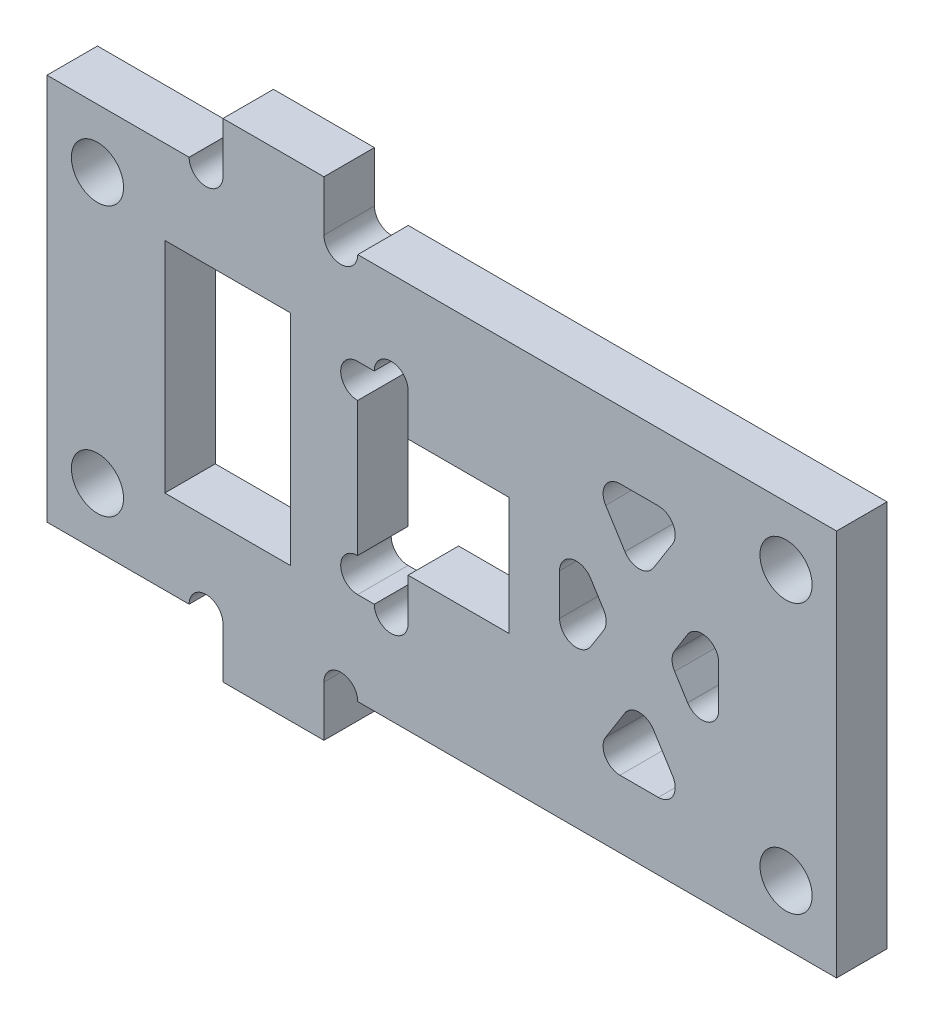
SolidWorks part; units mm, degrees
material "Thornel Mat VMA"
ref_plane "前视基准面" through (0, 0, 0) normal (0, 0, 1) x (1, 0, 0)
ref_plane "上视基准面" through (0, 0, 0) normal (0, 1, 0) x (1, 0, 0)
ref_plane "右视基准面" through (0, 0, 0) normal (1, 0, 0) x (0, 0, -1)
sketch "草图1" plane through (0, 0, 0) normal (0, 0, 1) x (1, 0, 0)
  line L0 (-13, 11.5) -> (-13, 14.5)
  line L1 (23.455, -11.5) -> (-7, -11.5)
  line L2 (23.455, -11.5) -> (23.455, 11.5)
  line L3 (23.455, 11.5) -> (-7, 11.5)
  line L4 (-23.455, -11.5) -> (-23.455, 11.5)
  line L5 (23.455, -11.5) -> (-23.455, 11.5) construction
  line L6 (23.455, 11.5) -> (-23.455, -11.5) construction
  line L7 (-20.455, 8) -> (-20.455, -8) construction
  line L8 (-20.455, 0) -> (0, 0) construction
  line L9 (0, 0) -> (0, 8.6559) construction
  line L10 (-2, -6) -> (-5, -6)
  line L11 (-2, -6) -> (-2, -3.5)
  line L12 (-2, 6) -> (-5, 6)
  line L13 (-5, -6) -> (-5, 6)
  line L14 (-2, -6) -> (-5, 6) construction
  line L15 (-2, 6) -> (-5, -6) construction
  line L16 (-13, 14.5) -> (-7, 14.5)
  line L17 (-7, 14.5) -> (-7, 11.5)
  line L18 (-13, 11.5) -> (-23.455, 11.5)
  line L19 (-7, -14.5) -> (-7, -11.5)
  line L20 (-13, -14.5) -> (-7, -14.5)
  line L21 (-13, -11.5) -> (-13, -14.5)
  line L22 (-13, -11.5) -> (-23.455, -11.5)
  line L23 (-2, -3.5) -> (4, -3.5)
  line L24 (4, -3.5) -> (4, 3.5)
  line L25 (4, 3.5) -> (-2, 3.5)
  line L26 (-2, 3.5) -> (-2, 6)
  line L27 (14.6819, -7.5) -> (11.7275, -2.813)
  line L28 (-9, 6.5) -> (-16.455, 6.5)
  line L29 (-9, 6.5) -> (-9, -6.5)
  line L30 (-9, -6.5) -> (-16.455, -6.5)
  line L31 (-16.455, 6.5) -> (-16.455, -6.5)
  line L32 (-9, 6.5) -> (-16.455, -6.5) construction
  line L33 (-9, -6.5) -> (-16.455, 6.5) construction
  line L34 (16.455, 7.5) -> (7, 7.5) construction
  line L35 (16.455, 7.5) -> (16.455, -7.5) construction
  line L36 (16.455, -7.5) -> (7, -7.5) construction
  line L37 (7, 7.5) -> (7, -7.5) construction
  line L38 (16.455, 7.5) -> (7, -7.5) construction
  line L39 (16.455, -7.5) -> (7, 7.5) construction
  line L40 (16.455, -4.687) -> (13.5006, 0)
  line L41 (7, -4.687) -> (9.9544, 0)
  line L42 (8.7731, -7.5) -> (11.7275, -2.813)
  line L43 (8.7731, -7.5) -> (14.6819, -7.5)
  line L44 (8.7731, 7.5) -> (14.6819, 7.5)
  line L45 (16.455, -4.687) -> (16.455, 4.687)
  line L46 (7, -4.687) -> (7, 4.687)
  line L47 (9.9544, 0) -> (7, 4.687)
  line L48 (13.5006, 0) -> (16.455, 4.687)
  line L49 (11.7275, 2.813) -> (8.7731, 7.5)
  line L50 (11.7275, 2.813) -> (14.6819, 7.5)
  circle A0 centre (-20.455, 8) radius 1.55
  circle A1 centre (-20.455, -8) radius 1.55
  circle A4 centre (20.455, -8) radius 1.55
  circle A5 centre (20.455, 8) radius 1.55
  circle A6 centre (-2, 4.995) radius 1.005 construction
  circle A7 centre (-5, 4.995) radius 1.005
  circle A8 centre (-5, -4.995) radius 1.005
  circle A9 centre (-2, -4.995) radius 1.005 construction
  circle A10 centre (-5.995, 11.5) radius 1.005
  circle A11 centre (-14.005, 11.5) radius 1.005
  circle A12 centre (-5.995, -11.5) radius 1.005
  circle A13 centre (-14.005, -11.5) radius 1.005
  circle A14 centre (-3.005, -6) radius 1.005
  circle A15 centre (-3.005, 6) radius 1.005
  point P0 (0, 0)
  point P7 (-3.5, 0)
  point P50 (-12.7275, 0)
  point P56 (11.7275, 0)
  dimension "D1" = 3.1
  dimension "D9" = 2.01
  dimension "D2" = 16
  dimension "D3" = 23
  dimension "D4" = 3
  dimension "D5" = 3
  dimension "D6" = 2
  dimension "D7" = 12
  dimension "D8" = 40.91
  dimension "D10" = 6
  dimension "D11" = 2
  dimension "D12" = 3
  dimension "D13" = 6
  dimension "D14" = 7
  dimension "D15" = 4
  dimension "D16" = 4
  dimension "D17" = 5
  dimension "D18" = 3
  dimension "D19" = 4
  dimension "D20" = 4
  dimension "D21" = 3
  dimension "D22" = 1.5
extrude "凸台-拉伸1" add sketch "草图1" along normal blind 3 contours A11 L18 L4 L1 L2 L3 A10 L17 L16 L0 A9 L10 A8 L13 A7 L12 A6 L11 A4 A1 A0 A5
fillet "圆角1" radius 1 12 edges at (16.455, 4.687, 1.5) (13.5006, 0, 1.5) (16.455, -4.687, 1.5) (14.6819, 7.5, 1.5) (8.7731, 7.5, 1.5) (11.7275, 2.813, 1.5) (7, 4.687, 1.5) (9.9544, 0, 1.5) (7, -4.687, 1.5) (14.6819, -7.5, 1.5) (11.7275, -2.813, 1.5) (8.7731, -7.5, 1.5)
